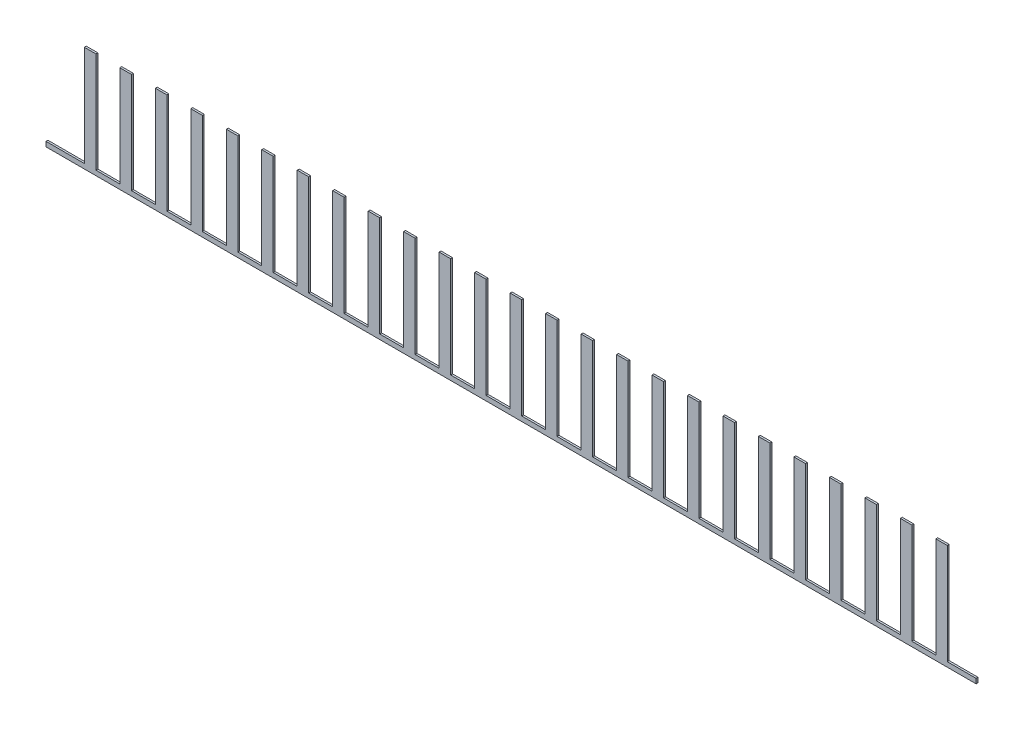
SolidWorks part; units mm, degrees
material "AISI 4130 Steel, annealed at 865C"
ref_plane "Front Plane" through (0, 0, 0) normal (0, 0, 1) x (1, 0, 0)
ref_plane "Top Plane" through (0, 0, 0) normal (0, 1, 0) x (1, 0, 0)
ref_plane "Right Plane" through (0, 0, 0) normal (1, 0, 0) x (0, 0, -1)
sketch "Sketch1" plane through (0, 0, 0) normal (0, 0, 1) x (1, 0, 0)
  line L0 (-481.4555, 0) -> (478.5445, 0)
  line L1 (-439.4555, 110) -> (-439.4555, 5)
  line L2 (436.5445, 110) -> (448.5445, 110)
  line L3 (-414.4555, 110) -> (-414.4555, 5)
  line L4 (-402.4555, 110) -> (-402.4555, 5)
  line L5 (-377.4555, 110) -> (-377.4555, 5)
  line L6 (-365.4555, 110) -> (-365.4555, 5)
  line L7 (-340.4555, 110) -> (-340.4555, 5)
  line L8 (-328.4555, 110) -> (-328.4555, 5)
  line L9 (-303.4555, 110) -> (-303.4555, 5)
  line L10 (-291.4555, 110) -> (-291.4555, 5)
  line L11 (-266.4555, 110) -> (-266.4555, 5)
  line L12 (-254.4555, 110) -> (-254.4555, 5)
  line L13 (-229.4555, 110) -> (-229.4555, 5)
  line L14 (-217.4555, 110) -> (-217.4555, 5)
  line L15 (-192.4555, 110) -> (-192.4555, 5)
  line L16 (-180.4555, 110) -> (-180.4555, 5)
  line L17 (-155.4555, 110) -> (-155.4555, 5)
  line L18 (-143.4555, 110) -> (-143.4555, 5)
  line L19 (-118.4555, 110) -> (-118.4555, 5)
  line L20 (-106.4555, 110) -> (-106.4555, 5)
  line L21 (-81.4555, 110) -> (-81.4555, 5)
  line L22 (-69.4555, 110) -> (-69.4555, 5)
  line L23 (-44.4555, 110) -> (-44.4555, 5)
  line L24 (-32.4555, 110) -> (-32.4555, 5)
  line L25 (-7.4555, 110) -> (-7.4555, 5)
  line L26 (4.5445, 110) -> (4.5445, 5)
  line L27 (29.5445, 110) -> (29.5445, 5)
  line L28 (41.5445, 110) -> (41.5445, 5)
  line L29 (66.5445, 110) -> (66.5445, 5)
  line L30 (78.5445, 110) -> (78.5445, 5)
  line L31 (103.5445, 110) -> (103.5445, 5)
  line L32 (115.5445, 110) -> (115.5445, 5)
  line L33 (140.5445, 110) -> (140.5445, 5)
  line L34 (152.5445, 110) -> (152.5445, 5)
  line L35 (177.5445, 110) -> (177.5445, 5)
  line L36 (189.5445, 110) -> (189.5445, 5)
  line L37 (214.5445, 110) -> (214.5445, 5)
  line L38 (226.5445, 110) -> (226.5445, 5)
  line L39 (251.5445, 110) -> (251.5445, 5)
  line L40 (263.5445, 110) -> (263.5445, 5)
  line L41 (288.5445, 110) -> (288.5445, 5)
  line L42 (300.5445, 110) -> (300.5445, 5)
  line L43 (325.5445, 110) -> (325.5445, 5)
  line L44 (337.5445, 110) -> (337.5445, 5)
  line L45 (362.5445, 110) -> (362.5445, 5)
  line L46 (374.5445, 110) -> (374.5445, 5)
  line L47 (399.5445, 110) -> (399.5445, 5)
  line L50 (3.5445, 70) -> (478.5445, -27.9381) construction
  line L51 (3.5445, 70) -> (78.5445, 85.625) construction
  line L54 (399.5445, 5) -> (374.5445, 5)
  line L55 (362.5445, 110) -> (374.5445, 110)
  line L56 (362.5445, 5) -> (337.5445, 5)
  line L57 (325.5445, 110) -> (337.5445, 110)
  line L58 (325.5445, 5) -> (300.5445, 5)
  line L59 (288.5445, 110) -> (300.5445, 110)
  line L60 (288.5445, 5) -> (263.5445, 5)
  line L61 (251.5445, 110) -> (263.5445, 110)
  line L62 (251.5445, 5) -> (226.5445, 5)
  line L63 (214.5445, 110) -> (226.5445, 110)
  line L64 (214.5445, 5) -> (189.5445, 5)
  line L65 (177.5445, 110) -> (189.5445, 110)
  line L66 (177.5445, 5) -> (152.5445, 5)
  line L67 (140.5445, 110) -> (152.5445, 110)
  line L68 (140.5445, 5) -> (115.5445, 5)
  line L69 (103.5445, 110) -> (115.5445, 110)
  line L70 (103.5445, 5) -> (78.5445, 5)
  line L71 (66.5445, 110) -> (78.5445, 110)
  line L72 (66.5445, 5) -> (41.5445, 5)
  line L73 (29.5445, 110) -> (41.5445, 110)
  line L74 (29.5445, 5) -> (4.5445, 5)
  line L75 (-7.4555, 110) -> (4.5445, 110)
  line L76 (-7.4555, 5) -> (-32.4555, 5)
  line L77 (-44.4555, 110) -> (-32.4555, 110)
  line L78 (-44.4555, 5) -> (-69.4555, 5)
  line L79 (-81.4555, 110) -> (-69.4555, 110)
  line L80 (-81.4555, 5) -> (-106.4555, 5)
  line L81 (-118.4555, 110) -> (-106.4555, 110)
  line L82 (-118.4555, 5) -> (-143.4555, 5)
  line L83 (-155.4555, 110) -> (-143.4555, 110)
  line L84 (-155.4555, 5) -> (-180.4555, 5)
  line L85 (-192.4555, 110) -> (-180.4555, 110)
  line L86 (-192.4555, 5) -> (-217.4555, 5)
  line L87 (-229.4555, 110) -> (-217.4555, 110)
  line L88 (-229.4555, 5) -> (-254.4555, 5)
  line L89 (-266.4555, 110) -> (-254.4555, 110)
  line L90 (-266.4555, 5) -> (-291.4555, 5)
  line L91 (-303.4555, 110) -> (-291.4555, 110)
  line L92 (-303.4555, 5) -> (-328.4555, 5)
  line L93 (-340.4555, 110) -> (-328.4555, 110)
  line L94 (-340.4555, 5) -> (-365.4555, 5)
  line L95 (-377.4555, 110) -> (-365.4555, 110)
  line L96 (-377.4555, 5) -> (-402.4555, 5)
  line L97 (-414.4555, 110) -> (-402.4555, 110)
  line L98 (-414.4555, 5) -> (-439.4555, 5)
  line L99 (-451.4555, 110) -> (-439.4555, 110)
  line L100 (448.5445, 110) -> (448.5445, 5)
  line L101 (448.5445, 5) -> (478.5445, 5)
  line L102 (8.5445, -25) -> (3.5445, -25) construction
  line L103 (-451.4555, 110) -> (-451.4555, 5)
  line L104 (-451.4555, 5) -> (-491.4555, 5)
  line L105 (-491.4555, 5) -> (-491.4555, 0)
  line L106 (-491.4555, 0) -> (-481.4555, 0)
  line L107 (478.5445, 5) -> (478.5445, 0)
  line L108 (399.5445, 110) -> (411.5445, 110)
  line L109 (411.5445, 110) -> (411.5445, 5)
  line L110 (436.5445, 110) -> (436.5445, 5)
  line L111 (436.5445, 5) -> (411.5445, 5)
  point P5 (3.5445, 70)
  point P99 (3.5445, -30)
  point P102 (-1.4555, 0)
  dimension "D1" = 960
  dimension "D3" = 40
extrude "Boss-Extrude1" add sketch "Sketch1" along normal blind 2
